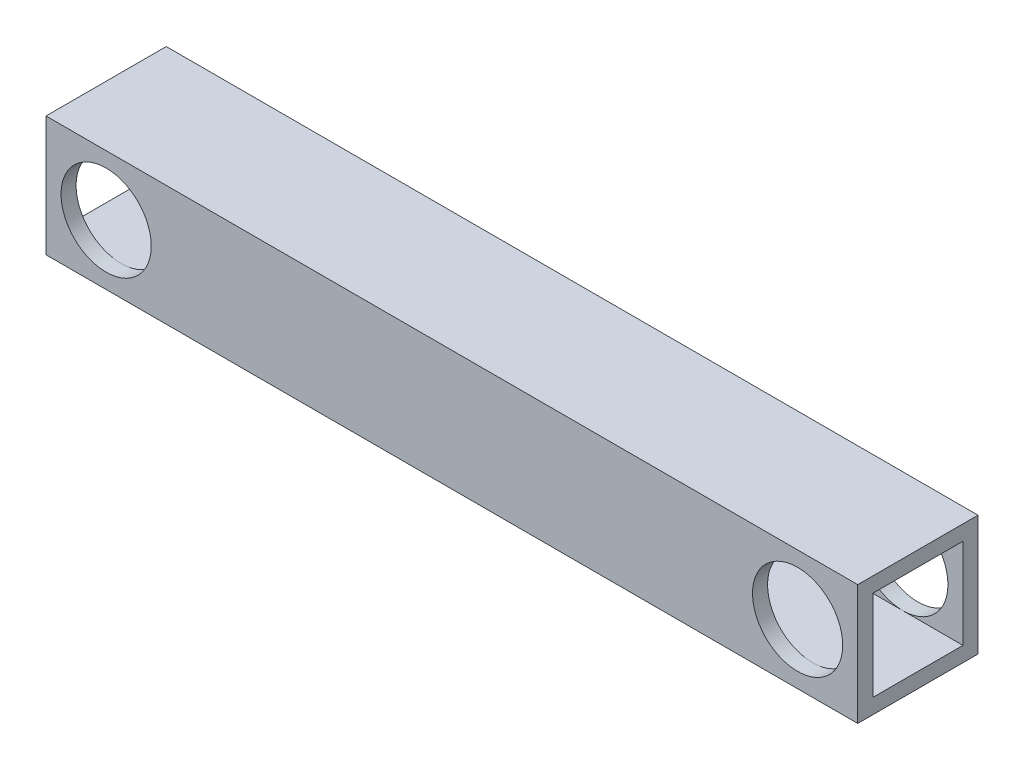
SolidWorks part; units mm, degrees
ref_plane "Front Plane" through (0, 0, 0) normal (0, 0, 1) x (1, 0, 0)
ref_plane "Top Plane" through (0, 0, 0) normal (0, 1, 0) x (1, 0, 0)
ref_plane "Right Plane" through (0, 0, 0) normal (1, 0, 0) x (0, 0, -1)
sketch "Sketch1" plane through (0, 0, 0) normal (0, 0, 1) x (1, 0, 0)
  line L0 (-12.7, 0) -> (0, 0) construction
  line L1 (158.75, 12.7) -> (-12.7, 12.7)
  line L2 (158.75, 12.7) -> (158.75, -12.7)
  line L3 (158.75, -12.7) -> (-12.7, -12.7)
  line L4 (-12.7, 12.7) -> (-12.7, -12.7)
  line L5 (0, 0) -> (0, -12.7) construction
  line L6 (146.05, 0) -> (158.75, 0) construction
  line L7 (146.05, 0) -> (146.05, -12.7) construction
  circle A0 centre (0, 0) radius 9.525
  circle A1 centre (146.05, 0) radius 9.525
  dimension "D2" = 19.05
  dimension "D3" = 146.05
  dimension "D4" = 19.05
  dimension "D1" = 25.4
extrude "Boss-Extrude1" add sketch "Sketch1" along normal blind 25.4
sketch "Sketch2" plane through (158.75, 0, 0) normal (1, 0, 0) x (0, 0, -1)
  line L8 (-3.175, -9.525) -> (-3.175, 9.525)
  line L9 (-3.175, 9.525) -> (-22.225, 9.525)
  line L10 (-22.225, 9.525) -> (-22.225, -9.525)
  line L11 (-22.225, -9.525) -> (-3.175, -9.525)
  line L12 (-3.175, -9.525) -> (-3.175, 9.525)
  line L13 (-3.175, 9.525) -> (-22.225, 9.525)
  line L14 (-22.225, 9.525) -> (-22.225, -9.525)
  line L15 (-22.225, -9.525) -> (-3.175, -9.525)
  dimension "D1" = 3.175
extrude "Cut-Extrude1" cut sketch "Sketch2" against normal through all
